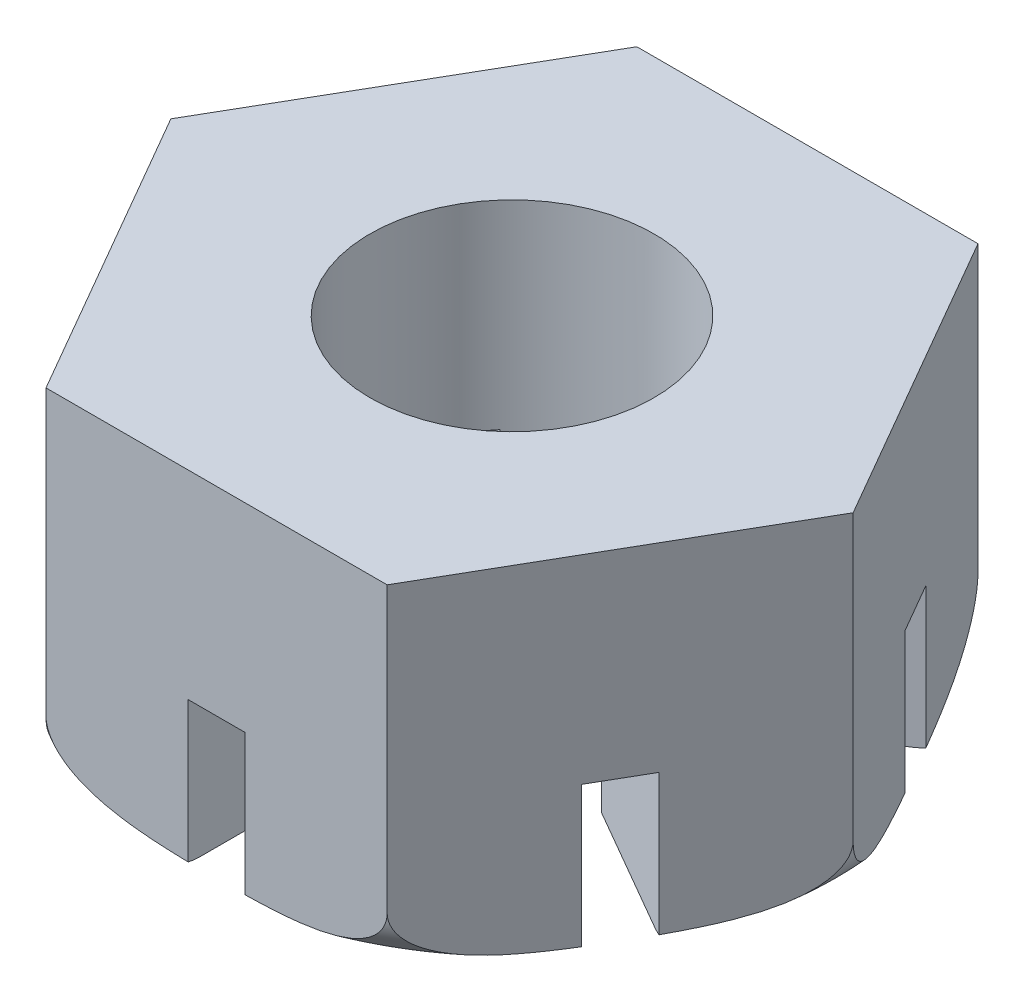
SolidWorks part; units mm, degrees
ref_plane "Front Plane" through (0, 0, 0) normal (0, 0, 1) x (1, 0, 0)
ref_plane "Top Plane" through (0, 0, 0) normal (0, 1, 0) x (1, 0, 0)
ref_plane "Right Plane" through (0, 0, 0) normal (1, 0, 0) x (0, 0, -1)
sketch "Sketch1" plane through (0, 0, 0) normal (0, 1, 0) x (1, 0, 0)
  line L0 (-60.0444, 0) -> (60.0444, 0)
  line L1 (30.0222, -52) -> (60.0444, 0)
  line L2 (60.0444, 0) -> (30.0222, 52)
  line L3 (30.0222, 52) -> (-30.0222, 52)
  line L4 (-30.0222, 52) -> (-60.0444, 0)
  line L5 (-60.0444, 0) -> (-30.0222, -52)
  line L6 (-30.0222, -52) -> (30.0222, -52)
  circle A0 centre (0, 0) radius 52 construction
  circle A1 centre (0, 0) radius 25.0005
  dimension "D2" = 50.001
  dimension "D1" = 104
extrude "Boss-Extrude1" add sketch "Sketch1" against normal blind 60 contours A1 L0 L5 L6 L1 | A1 L0 L2 L3 L4
sketch "Sketch2" plane through (0, -60, 0) normal (0, -1, 0) x (1, 0, 0)
  line L0 (0, 52) -> (0, -52) construction
  line L1 (-30.0222, 52) -> (30.0222, 52) construction
  line L2 (30.0222, -52) -> (-30.0222, -52) construction
  line L3 (-5, 52) -> (-5, 24.4954)
  line L4 (5, 52) -> (5, 24.4954)
  line L5 (-5, 52) -> (5, 52)
  line L6 (42.5333, 30.3301) -> (18.7137, 16.5778)
  line L7 (42.5333, 30.3301) -> (47.5333, 21.6699)
  line L8 (47.5333, 21.6699) -> (23.7137, 7.9176)
  line L9 (47.5333, -21.6699) -> (23.7137, -7.9176)
  line L10 (47.5333, -21.6699) -> (42.5333, -30.3301)
  line L11 (42.5333, -30.3301) -> (18.7137, -16.5778)
  line L12 (5, -52) -> (5, -24.4954)
  line L13 (5, -52) -> (-5, -52)
  line L14 (-5, -52) -> (-5, -24.4954)
  line L15 (-42.5333, -30.3301) -> (-18.7137, -16.5778)
  line L16 (-42.5333, -30.3301) -> (-47.5333, -21.6699)
  line L17 (-47.5333, -21.6699) -> (-23.7137, -7.9176)
  line L18 (-47.5333, 21.6699) -> (-23.7137, 7.9176)
  line L19 (-47.5333, 21.6699) -> (-42.5333, 30.3301)
  line L20 (-42.5333, 30.3301) -> (-18.7137, 16.5778)
  line L21 (-30.0222, -52) -> (-60.0444, 0) construction
  circle A0 centre (0, 0) radius 25.0005 construction
  arc A1 (-18.7137, 16.5778) -> (-23.7137, 7.9176) centre (0, 0) ccw
  arc A2 (5, 24.4954) -> (-5, 24.4954) centre (0, 0) ccw
  arc A3 (23.7137, 7.9176) -> (18.7137, 16.5778) centre (0, 0) ccw
  arc A4 (18.7137, -16.5778) -> (23.7137, -7.9176) centre (0, 0) ccw
  arc A5 (-5, -24.4954) -> (5, -24.4954) centre (0, 0) ccw
  arc A6 (-23.7137, -7.9176) -> (-18.7137, -16.5778) centre (0, 0) ccw
  point P34 (0, 0)
  dimension "D1" = 10
  dimension "D2" = 6
extrude "Cut-Extrude1" cut sketch "Sketch2" against normal blind 25
sketch "Sketch5" plane through (0, 0, 0) normal (0, 0, 1) x (1, 0, 0)
  line L0 (0, 0) -> (0, -63.9093)
  line L1 (-30.0222, 0) -> (30.0222, 0) construction
  line L2 (50.0444, -60) -> (50.0444, -50) construction
  line L3 (47.5333, -60) -> (60.0444, -60) construction
  line L4 (50.0444, -50) -> (60.0444, -50) construction
  line L5 (60.0444, -60) -> (60.0444, 0) construction
  line L6 (60.0444, -50) -> (66.9959, -50)
  line L7 (66.9959, -50) -> (66.9959, -66.9025)
  line L8 (66.9959, -66.9025) -> (50.0444, -66.9025)
  line L9 (50.0444, -66.9025) -> (50.0444, -60)
  arc A0 (60.0444, -50) -> (50.0444, -60) centre (50.0444, -50) cw
  point P12 (66.9959, -66.9025)
  dimension "D1" = 10
revolve "Cut-Revolve3" cut sketch "Sketch5" angle 360 about L0
